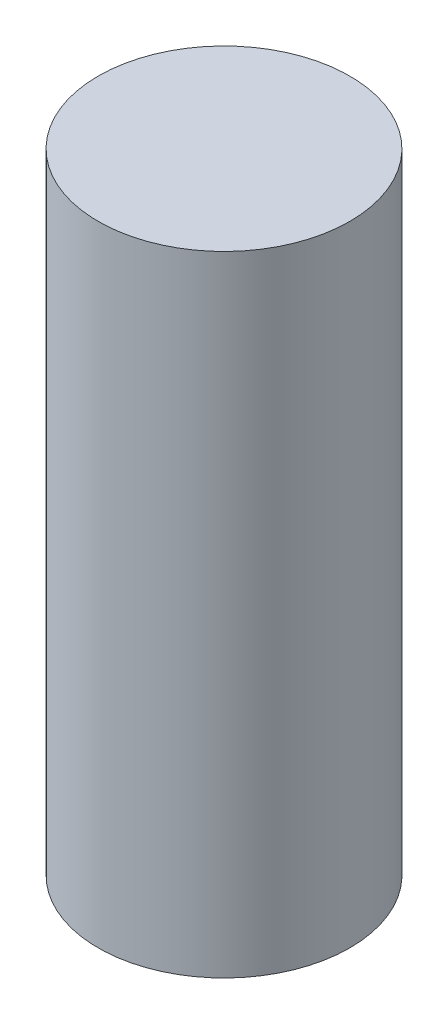
SolidWorks part; units mm, degrees
ref_plane "前视基准面" through (0, 0, 0) normal (0, 0, 1) x (1, 0, 0)
ref_plane "上视基准面" through (0, 0, 0) normal (0, 1, 0) x (1, 0, 0)
ref_plane "右视基准面" through (0, 0, 0) normal (1, 0, 0) x (0, 0, -1)
sketch "草图1" plane through (0, 22.5, 0) normal (0, 1, 0) x (1, 0, 0)
  circle A0 centre (39.5, 0) radius 2
  dimension "D1" = 4
extrude "凸台-拉伸1" add sketch "草图1" along normal blind 10
